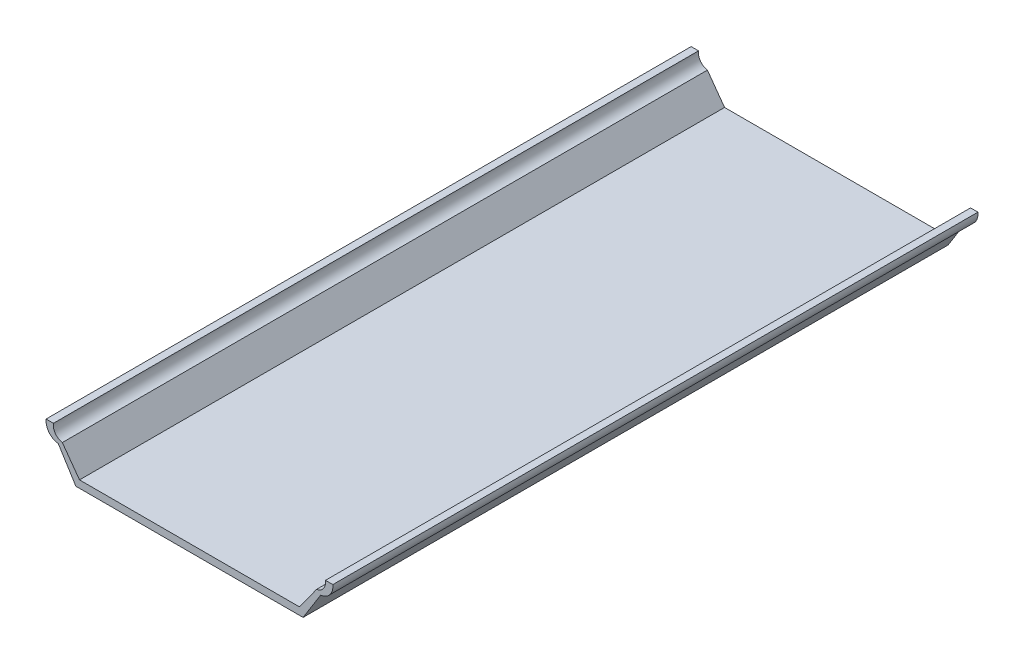
SolidWorks part; units mm, degrees
ref_plane "Plan de face" through (0, 0, 0) normal (0, 0, 1) x (1, 0, 0)
ref_plane "Plan de dessus" through (0, 0, 0) normal (0, 1, 0) x (1, 0, 0)
ref_plane "Plan de droite" through (0, 0, 0) normal (1, 0, 0) x (0, 0, -1)
sketch "Esquisse1" plane through (0, 0, 0) normal (0, 0, 1) x (1, 0, 0)
  line L0 (-15, 0) -> (15, 0)
  line L1 (-15, 0) -> (-17.3449, 3.2406)
  line L2 (-15.5, -1) -> (15.5, -1)
  line L3 (15, 0) -> (17.3449, 3.2406)
  line L4 (0, 0) -> (0, -1)
  line L5 (-18.5549, 4.9126) -> (-19.5601, 4.9126)
  line L6 (18.5549, 4.9126) -> (19.5601, 4.9126)
  line L10 (-15.5, -1) -> (-17.9009, 2.8382)
  line L11 (15.5, -1) -> (17.9009, 2.8382)
  arc A0 (-17.3449, 3.2406) -> (-18.5549, 4.9126) centre (-17.1139, 4.6815) cw
  arc A1 (17.3449, 3.2406) -> (18.5549, 4.9126) centre (17.1139, 4.6815) ccw
  arc A2 (19.5601, 4.9126) -> (17.9009, 2.8382) centre (17.6933, 4.705) cw
  arc A3 (-19.5601, 4.9126) -> (-17.9009, 2.8382) centre (-17.6933, 4.705) ccw
  point P4 (0, 0)
  point P21 (0, -1)
  dimension "D1" = 30
  dimension "D2" = 4
  dimension "D3" = 1
  dimension "D4" = 31
extrude "Boss.-Extru.1" add sketch "Esquisse1" along normal blind 88
sketch "Esquisse2" plane through (0, -1, 0) normal (0, -1, 0) x (1, 0, 0)
  line L0 (0, 88) -> (0, 80)
  line L1 (-15.5, 88) -> (15.5, 88) construction
  line L2 (0, 0) -> (0, 10)
  circle A0 centre (0, 10) radius 2
  circle A1 centre (0, 80) radius 2
  dimension "D3" = 4
  dimension "D4" = 4
  dimension "D1" = 10
  dimension "D2" = 8
extrude "Enlèv. mat.-Extru.2" [suppressed] cut sketch "Esquisse2" against normal blind 10 contours A1 | A0
